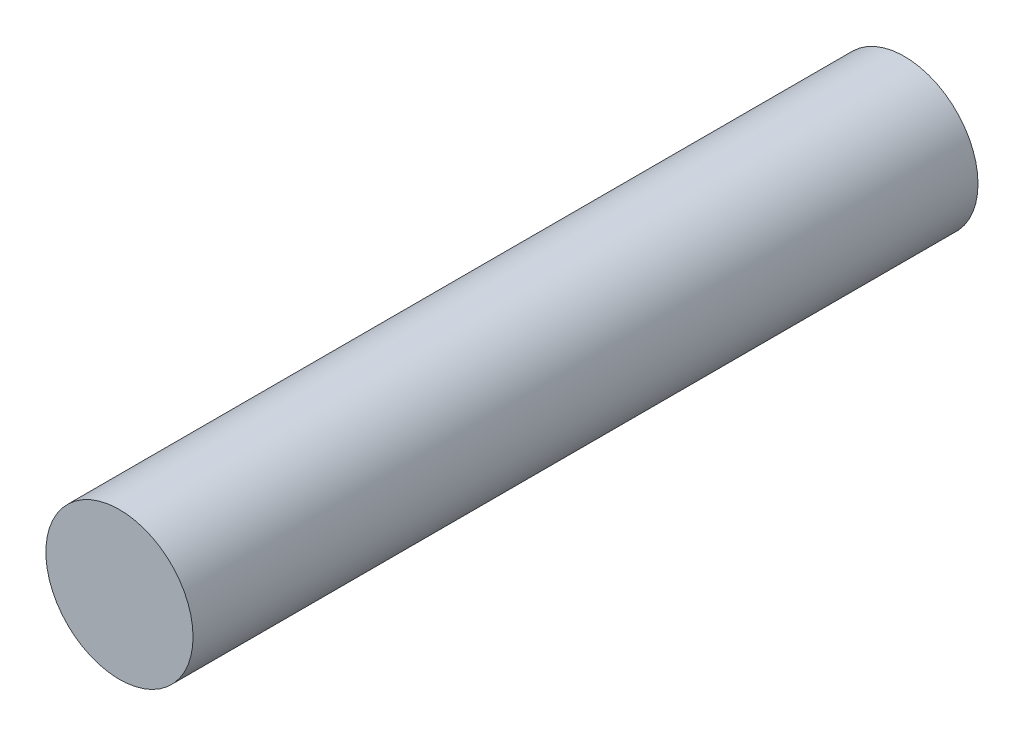
SolidWorks part; units mm, degrees
ref_plane "Front Plane" through (0, 0, 0) normal (0, 0, 1) x (1, 0, 0)
ref_plane "Top Plane" through (0, 0, 0) normal (0, 1, 0) x (1, 0, 0)
ref_plane "Right Plane" through (0, 0, 0) normal (1, 0, 0) x (0, 0, -1)
sketch "Sketch1" plane through (0, 0, 0) normal (0, 0, 1) x (1, 0, 0)
  circle A0 centre (0, 0) radius 4.7625
  dimension "D1" = 9.525
extrude "Boss-Extrude1" add sketch "Sketch1" along normal blind 50.8
